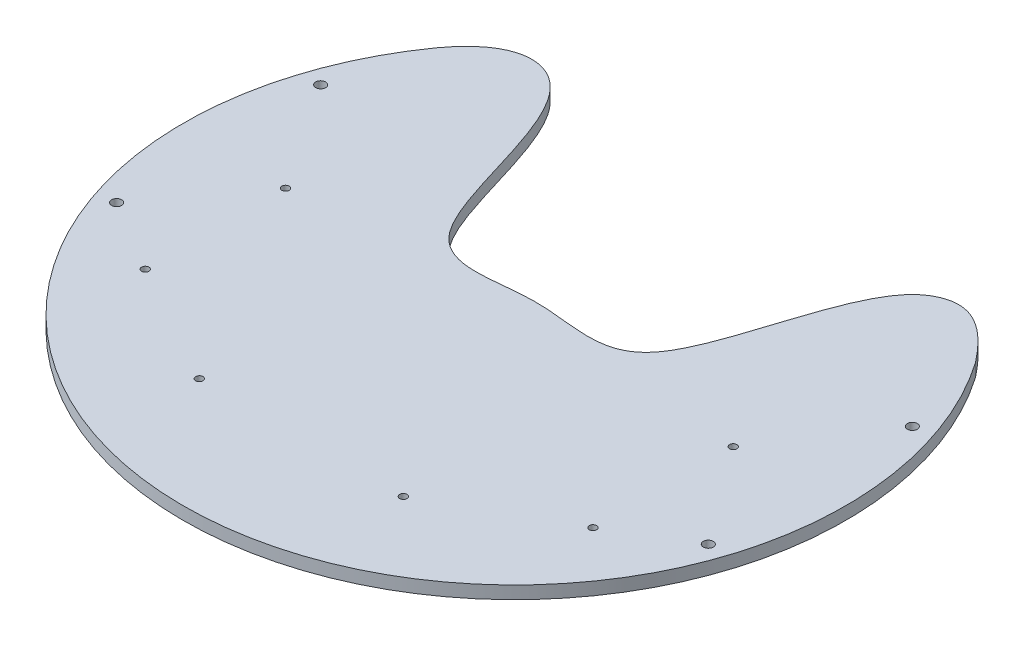
SolidWorks part; units mm, degrees
material "ABS"
ref_plane "Front Plane" through (0, 0, 0) normal (0, 0, 1) x (1, 0, 0)
ref_plane "Top Plane" through (0, 0, 0) normal (0, 1, 0) x (1, 0, 0)
ref_plane "Right Plane" through (0, 0, 0) normal (1, 0, 0) x (0, 0, -1)
sketch "Sketch1" plane through (0, 0, 0) normal (0, 1, 0) x (1, 0, 0)
  circle A0 centre (0, 0) radius 164.975
  dimension "D1" = 329.95
extrude "Boss-Extrude1" add sketch "Sketch1" along normal blind 6.35
ref_point "Point1"
hole_wizard "#6 Clearance Hole1" positions "3DSketch1" profile "Sketch2" hole size "#6" standard "Ansi Inch" end condition through all
sketch3d "3DSketch1"
  line L0 (0, 0, 0) -> (213.1626, 0, 0) construction
  line L2 (0, 0, 0) -> (0, 0, 209.6006) construction
  point P20 (111.465, 0, 2.54)
  point P22 (111.465, 0, 72.39)
  point P26 (111.465, 0, 2.54)
  point P28 (-111.465, 0, 72.39)
  point P29 (-111.465, 0, 2.54)
  dimension "D1" = 2.54
  dimension "D2" = 111.465
  dimension "D3" = 111.465
  dimension "D4" = 69.85
  dimension "D5" = 111.465
  dimension "D6" = 2.54
  dimension "D7" = 69.85
  dimension "D8" = 111.465
sketch "Sketch2" plane through (111.465, 0, 2.54) normal (1, 0, 0) x (0, 0, -1)
  line L0 (0, 0) -> (0, 6.35)
  line L1 (0, 6.35) -> (1.8288, 6.35)
  line L2 (1.8288, 6.35) -> (1.8288, 0)
  line L5 (1.8288, 0) -> (0, 0)
  line L11 (0, -6.35) -> (0, 107.95) construction
  dimension "Thru Hole Dia." = 3.6576
  dimension "Thru Hole Depth" = 6.35
sketch "Sketch4" plane through (0, 6.35, 0) normal (0, 1, 0) x (1, 0, 0)
  line L0 (-50.8, -156.9589) -> (50.8, -156.9589) construction
  line L1 (-50.8, -156.9589) -> (50.8, -156.9589) construction
  line L2 (-50.8, -156.9589) -> (-50.8, -55.3589) construction
  line L3 (50.8, -156.9589) -> (50.8, -55.3589) construction
  line L4 (-50.8, -55.3589) -> (50.8, -55.3589) construction
  line L5 (-50.8, -55.3589) -> (50.8, -156.9589) construction
  line L6 (50.8, -55.3589) -> (-50.8, -156.9589) construction
  line L7 (0, -106.1589) -> (0, 10.6811) construction
  line L8 (0, -106.1589) -> (0, -164.975) construction
  circle A0 centre (0, 0) radius 164.975 construction
  spline S0 degree 3 poles (-135.5593, 94.0236) (-123.8657, 111.0772) (-106.45, 118.5854) (-71.3902, 97.7596) (-62.1016, -5.971) (0.172, 18.1838) (61.3362, -6.0535) (73.495, 97.956) (105.3342, 118.2208) (120.0537, 114.0069) (135.5593, 94.0236) knots 0 0 0 0 0.096823 0.130284 0.334615 0.50142 0.668226 0.872557 0.905734 1 1 1 1
  dimension "D1" = 7.62
  dimension "D2" = 7.62
  dimension "D3" = 96.52
  dimension "D4" = 96.52
  dimension "D5" = 101.6
  dimension "D6" = 101.6
  dimension "D7" = 58.8161
  dimension "D8" = 116.84
extrude "Cut-Extrude1" cut sketch "Sketch4" against normal through all and the other way through all
sketch "Sketch6" plane through (0, 6.35, 0) normal (0, 1, 0) x (1, 0, 0)
  line L1 (50.8, -55.3589) -> (-50.8, -55.3589) construction
  line L2 (50.8, -55.3589) -> (50.8, -156.9589) construction
  line L3 (50.8, -156.9589) -> (-50.8, -156.9589) construction
  line L4 (-50.8, -55.3589) -> (-50.8, -156.9589) construction
  line L5 (50.8, -55.3589) -> (-50.8, -156.9589) construction
  line L6 (50.8, -156.9589) -> (-50.8, -55.3589) construction
  arc A0 (-134.5149, 95.5117) -> (135.5593, 94.0236) centre (0, 0) ccw construction
  point P0 (0, -106.1589)
  point P8 (-50.8, -106.1589)
  point P9 (50.8, -106.1589)
hole_wizard "#6 Clearance Hole2" positions "3DSketch2" profile "Sketch7" hole size "#6" standard "Ansi Inch"
sketch3d "3DSketch2"
  point P0 (50.8, 6.35, 106.1589)
  point P3 (-50.8, 6.35, 106.1589)
sketch "Sketch7" plane through (50.8, 6.35, 106.1589) normal (1, 0, 0) x (0, 0, 1)
  line L0 (0, 0) -> (0, 26.4989)
  line L1 (0, 26.4989) -> (1.8288, 25.4)
  line L2 (1.8288, 25.4) -> (1.8288, 0)
  line L5 (1.8288, 0) -> (0, 0)
  line L10 (0, 26.4989) -> (-1.8288, 25.4) construction
  line L11 (0, -6.35) -> (0, 107.95) construction
  dimension "Hole Dia." = 3.6576
  dimension "Hole Depth" = 25.4
  dimension "Drill Angle" = 118
sketch "Sketch8" plane through (0, 6.35, 0) normal (0, 1, 0) x (1, 0, 0)
  line L0 (0, -1000) -> (0, 49000) construction
  line L1 (-147.32, 50.8) -> (-147.32, -50.8) construction
  circle A0 centre (-147.32, 50.8) radius 4.7625 construction
  circle A1 centre (-147.32, -50.8) radius 4.7625 construction
  circle A2 centre (147.32, -50.8) radius 4.7625 construction
  circle A3 centre (147.32, 50.8) radius 4.7625 construction
  point P1 (-147.32, 50.8)
  point P4 (-147.32, -50.8)
  point P13 (147.32, 50.8)
  dimension "D1" = 50.8
  dimension "D2" = 50.8
  dimension "D3" = 147.32
  dimension "D4" = 50.8
  dimension "D5" = 147.32
hole_wizard "#10 Clearance Hole3" positions "Sketch16" profile "Sketch17" hole size "#10" standard "Ansi Inch" end condition through all
sketch "Sketch16" plane through (0, 6.35, 0) normal (0, 1, 0) x (-1, 0, 0)
  point P1 (147.32, -50.8)
  point P4 (147.32, 50.8)
  point P7 (-147.32, -50.8)
  point P10 (-147.32, 50.8)
sketch "Sketch17" plane through (-147.32, 6.35, -50.8) normal (1, 0, 0) x (0, 0, 1)
  line L0 (0, 0) -> (0, 6.35)
  line L1 (0, 6.35) -> (2.4892, 6.35)
  line L2 (2.4892, 6.35) -> (2.4892, 0)
  line L5 (2.4892, 0) -> (0, 0)
  line L11 (0, -6.35) -> (0, 107.95) construction
  dimension "Thru Hole Dia." = 4.9784
  dimension "Thru Hole Depth" = 6.35
